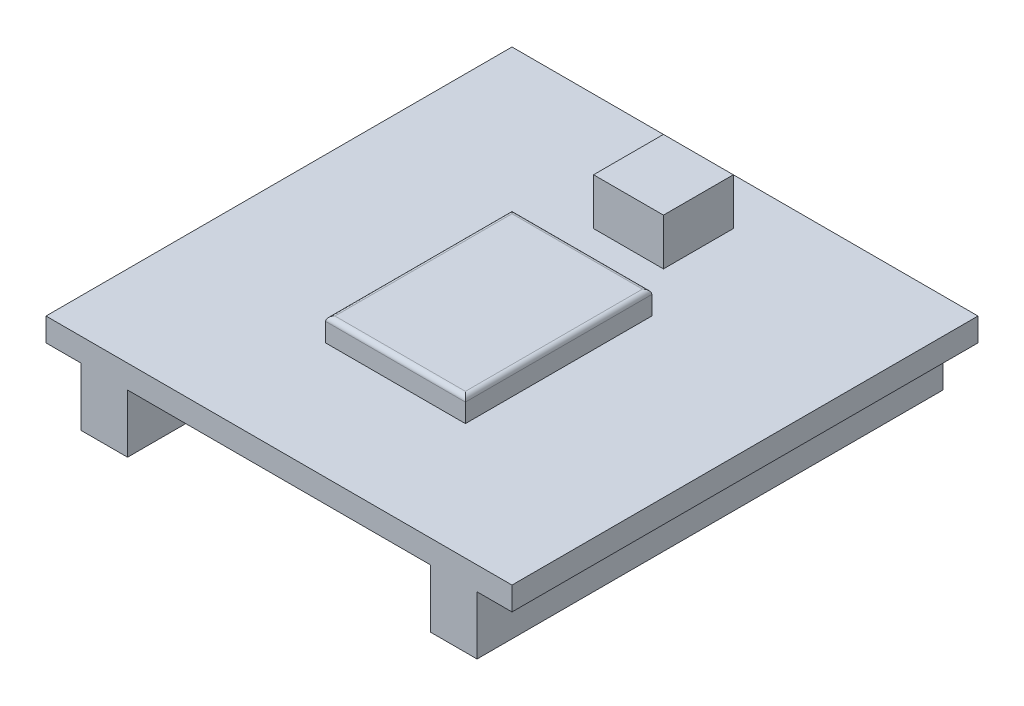
SolidWorks part; units mm, degrees
ref_plane "Alzado" through (0, 0, 0) normal (0, 0, 1) x (1, 0, 0)
ref_plane "Planta" through (0, 0, 0) normal (0, 1, 0) x (1, 0, 0)
ref_plane "Vista lateral" through (0, 0, 0) normal (1, 0, 0) x (0, 0, -1)
sketch "Croquis1" plane through (0, 0, 0) normal (0, 1, 0) x (1, 0, 0)
  line L1 (-10, -10) -> (10, -10)
  line L2 (-10, -10) -> (-10, 10)
  line L3 (-10, 10) -> (10, 10)
  line L4 (10, -10) -> (10, 10)
  line L5 (-10, -10) -> (10, 10) construction
  line L6 (-10, 10) -> (10, -10) construction
  point P0 (0, 0)
  dimension "D1" = 20
  dimension "D2" = 20
extrude "Saliente-Extruir1" add sketch "Croquis1" along normal blind 1
sketch "Croquis2" plane through (0, 1, 0) normal (0, 1, 0) x (1, 0, 0)
  line L0 (-10, 10) -> (-10, -10) construction
  line L1 (-3, 3) -> (3, 3)
  line L2 (-3, 3) -> (-3, -5)
  line L3 (-3, -5) -> (3, -5)
  line L4 (3, 3) -> (3, -5)
  line L5 (-3, 3) -> (3, -5) construction
  line L6 (-3, -5) -> (3, 3) construction
  line L7 (-10, -10) -> (10, -10) construction
  line L8 (10, -10) -> (10, 10) construction
  line L9 (10, 10) -> (-10, 10) construction
  point P0 (0, -1)
  dimension "D1" = 7
  dimension "D2" = 5
  dimension "D3" = 7
  dimension "D4" = 7
extrude "Saliente-Extruir2" add sketch "Croquis2" along normal blind 1
fillet "Redondeo1" radius 0.2 4 edges at (0, 2, 5) (-3, 2, 1) (0, 2, -3) (3, 2, 1)
sketch "Croquis3" plane through (0, 1, 0) normal (0, 1, 0) x (1, 0, 0)
  line L0 (10, 10) -> (-10, 10) construction
  line L1 (-1.5, 8) -> (1.5, 8)
  line L2 (-1.5, 8) -> (-1.5, 5)
  line L3 (-1.5, 5) -> (1.5, 5)
  line L4 (1.5, 8) -> (1.5, 5)
  line L5 (-1.5, 8) -> (1.5, 5) construction
  line L6 (-1.5, 5) -> (1.5, 8) construction
  line L7 (-10, 10) -> (-10, -10) construction
  line L8 (10, -10) -> (10, 10) construction
  point P0 (0, 6.5)
  dimension "D1" = 2
  dimension "D2" = 8.5
  dimension "D3" = 8.5
  dimension "D4" = 3
extrude "Saliente-Extruir3" add sketch "Croquis3" along normal blind 2
sketch "Croquis4" plane through (0, 0, 0) normal (0, -1, 0) x (1, 0, 0)
  line L0 (-10, 10) -> (10, 10) construction
  line L1 (-8.5, -10) -> (-6.5, -10)
  line L2 (-8.5, -10) -> (-8.5, 10)
  line L3 (-8.5, 10) -> (-6.5, 10)
  line L4 (-6.5, -10) -> (-6.5, 10)
  line L5 (-8.5, -10) -> (-6.5, 10) construction
  line L6 (-8.5, 10) -> (-6.5, -10) construction
  line L7 (-10, -10) -> (-10, 10) construction
  line L8 (0, 0) -> (0, 11.5847) construction
  line L9 (8.5, 10) -> (6.5, 10)
  line L10 (6.5, -10) -> (6.5, 10)
  line L11 (8.5, -10) -> (6.5, -10)
  line L12 (8.5, -10) -> (8.5, 10)
  point P0 (-7.5, 0)
  dimension "D1" = 2
  dimension "D2" = 20
  dimension "D3" = 1.5
extrude "Saliente-Extruir4" add sketch "Croquis4" along normal blind 2.5
